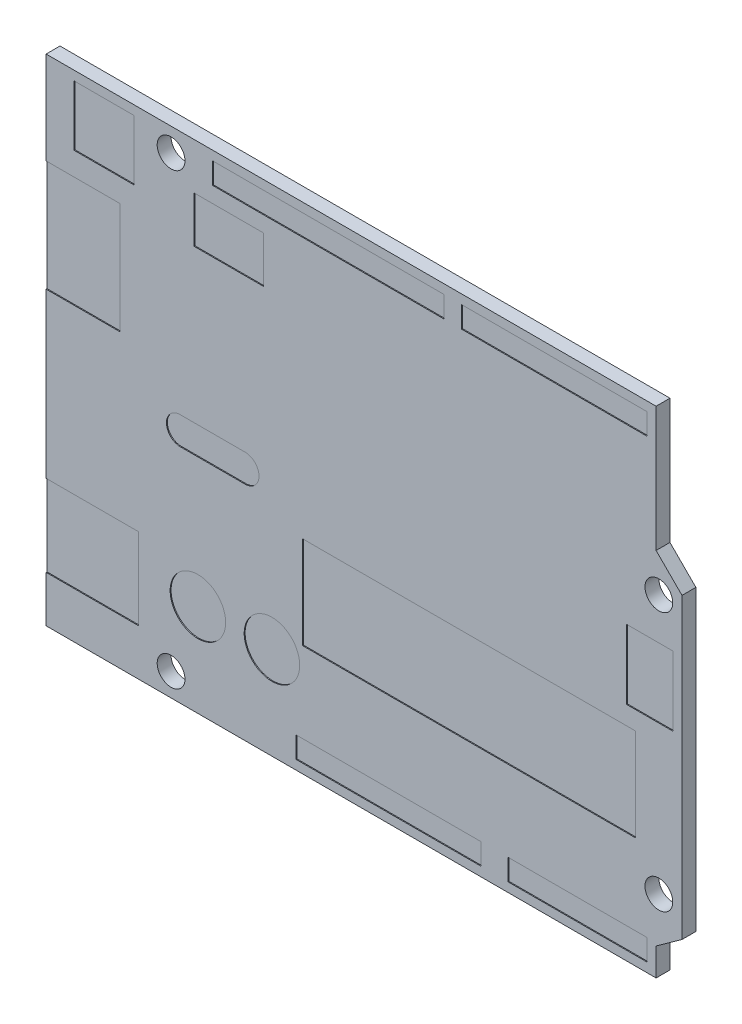
SolidWorks part; units mm, degrees
ref_plane "Plan de face" through (0, 0, 0) normal (0, 0, 1) x (1, 0, 0)
ref_plane "Plan de dessus" through (0, 0, 0) normal (0, 1, 0) x (1, 0, 0)
ref_plane "Plan de droite" through (0, 0, 0) normal (1, 0, 0) x (0, 0, -1)
sketch "Esquisse1" plane through (0, 0, 0) normal (0, 0, 1) x (1, 0, 0)
  line L0 (35.75, 10.45) -> (35.75, -21.75)
  line L1 (-32.95, -26.75) -> (32.95, -26.75)
  line L2 (-32.95, -26.75) -> (-32.95, 26.75)
  line L3 (-32.95, 26.75) -> (32.95, 26.75)
  line L4 (32.95, -26.75) -> (32.95, -23.75)
  line L5 (-32.95, -26.75) -> (32.95, 26.75) construction
  line L6 (-32.95, 26.75) -> (32.95, -26.75) construction
  line L7 (35.75, -21.75) -> (32.95, -23.75)
  line L8 (35.75, 10.45) -> (32.95, 13.25)
  line L9 (32.95, 13.25) -> (32.95, 26.75)
  line L10 (34.75, 8.9034) -> (34.75, -16.2642) construction
  line L11 (33.25, 9.25) -> (33.25, -18.75) construction
  line L12 (0, 0) -> (-23.2773, 0) construction
  circle A0 centre (33.25, 9.25) radius 1.5
  circle A1 centre (33.25, -18.75) radius 1.5
  circle A2 centre (-19.45, 24.25) radius 1.5
  circle A3 centre (-19.45, -24.25) radius 1.5
  point P0 (0, 0)
  dimension "D9" = 3
  dimension "D11" = 8
  dimension "D1" = 65.9
  dimension "D2" = 53.5
  dimension "D3" = 2.8
  dimension "D4" = 32.2
  dimension "D5" = 5
  dimension "D6" = 3
  dimension "D7" = 13.5
  dimension "D8" = 1
  dimension "D10" = 28
  dimension "D12" = 2.5
  dimension "D13" = 13.5
extrude "Boss.-Extru.1" add sketch "Esquisse1" along normal blind 1.5
sketch "Esquisse2" plane through (0, 0, 1.5) normal (0, 0, 1) x (1, 0, 0)
  line L0 (32.95, 26.75) -> (-32.95, 26.75) construction
  line L1 (-29.95, 25.75) -> (-23.45, 25.75)
  line L2 (-29.95, 25.75) -> (-29.95, 19.25)
  line L3 (-29.95, 19.25) -> (-23.45, 19.25)
  line L4 (-23.45, 25.75) -> (-23.45, 19.25)
  line L5 (-29.95, 25.75) -> (-23.45, 19.25) construction
  line L6 (-29.95, 19.25) -> (-23.45, 25.75) construction
  line L7 (-32.95, 26.75) -> (-32.95, -26.75) construction
  line L8 (-18.45, -1.25) -> (-11.45, -1.25) construction
  line L9 (-18.45, 0.25) -> (-11.45, 0.25)
  line L10 (-18.45, -2.75) -> (-11.45, -2.75)
  line L11 (-32.95, -26.75) -> (32.95, -26.75) construction
  line L12 (35.75, -21.75) -> (35.75, 10.45) construction
  line L13 (-5.25, -4.75) -> (30.75, -4.75)
  line L14 (-5.25, -4.75) -> (-5.25, -14.75)
  line L15 (-5.25, -14.75) -> (30.75, -14.75)
  line L16 (30.75, -4.75) -> (30.75, -14.75)
  line L17 (-5.25, -4.75) -> (30.75, -14.75) construction
  line L18 (-5.25, -14.75) -> (30.75, -4.75) construction
  line L19 (32.95, -26.75) -> (32.95, -23.75) construction
  line L20 (29.75, 4.75) -> (34.75, 4.75)
  line L21 (29.75, 4.75) -> (29.75, -2.75)
  line L22 (29.75, -2.75) -> (34.75, -2.75)
  line L23 (34.75, 4.75) -> (34.75, -2.75)
  line L24 (29.75, 4.75) -> (34.75, -2.75) construction
  line L25 (29.75, -2.75) -> (34.75, 4.75) construction
  line L26 (-5.95, -23.45) -> (14.05, -23.45)
  line L27 (-5.95, -23.45) -> (-5.95, -25.75)
  line L28 (-5.95, -25.75) -> (14.05, -25.75)
  line L29 (14.05, -23.45) -> (14.05, -25.75)
  line L30 (-5.95, -23.45) -> (14.05, -25.75) construction
  line L31 (-5.95, -25.75) -> (14.05, -23.45) construction
  line L32 (16.95, -23.45) -> (31.95, -23.45)
  line L33 (16.95, -23.45) -> (16.95, -25.75)
  line L34 (16.95, -25.75) -> (31.95, -25.75)
  line L35 (31.95, -23.45) -> (31.95, -25.75)
  line L36 (16.95, -23.45) -> (31.95, -25.75) construction
  line L37 (16.95, -25.75) -> (31.95, -23.45) construction
  line L38 (-33.7473, -12.95) -> (-22.95, -12.95)
  line L39 (-33.7473, -12.95) -> (-33.7473, -21.75)
  line L40 (-33.7473, -21.75) -> (-22.95, -21.75)
  line L41 (-22.95, -12.95) -> (-22.95, -21.75)
  line L42 (-33.7473, -12.95) -> (-22.95, -21.75) construction
  line L43 (-33.7473, -21.75) -> (-22.95, -12.95) construction
  line L44 (-36.8663, 16.75) -> (-24.95, 16.75)
  line L45 (-36.8663, 16.75) -> (-36.8663, 4.75)
  line L46 (-36.8663, 4.75) -> (-24.95, 4.75)
  line L47 (-24.95, 16.75) -> (-24.95, 4.75)
  line L48 (-36.8663, 16.75) -> (-24.95, 4.75) construction
  line L49 (-36.8663, 4.75) -> (-24.95, 16.75) construction
  line L50 (-14.95, 25.75) -> (10.05, 25.75)
  line L51 (-14.95, 25.75) -> (-14.95, 23.45)
  line L52 (-14.95, 23.45) -> (10.05, 23.45)
  line L53 (10.05, 25.75) -> (10.05, 23.45)
  line L54 (-14.95, 25.75) -> (10.05, 23.45) construction
  line L55 (-14.95, 23.45) -> (10.05, 25.75) construction
  line L56 (11.95, 25.75) -> (31.95, 25.75)
  line L57 (11.95, 25.75) -> (11.95, 23.45)
  line L58 (11.95, 23.45) -> (31.95, 23.45)
  line L59 (31.95, 25.75) -> (31.95, 23.45)
  line L60 (11.95, 25.75) -> (31.95, 23.45) construction
  line L61 (11.95, 23.45) -> (31.95, 25.75) construction
  line L63 (32.95, 13.25) -> (32.95, 26.75) construction
  line L65 (-16.95, 21.75) -> (-9.45, 21.75)
  line L66 (-16.95, 21.75) -> (-16.95, 16.75)
  line L67 (-16.95, 16.75) -> (-9.45, 16.75)
  line L68 (-9.45, 21.75) -> (-9.45, 16.75)
  line L69 (-16.95, 21.75) -> (-9.45, 16.75) construction
  line L70 (-16.95, 16.75) -> (-9.45, 21.75) construction
  arc A0 (-18.45, 0.25) -> (-18.45, -2.75) centre (-18.45, -1.25) ccw
  arc A1 (-11.45, -2.75) -> (-11.45, 0.25) centre (-11.45, -1.25) ccw
  circle A2 centre (-16.55, -16.75) radius 3
  circle A3 centre (-8.55, -16.75) radius 3
  point P0 (-26.7, 22.5)
  point P10 (-14.95, -1.25)
  point P16 (-19.95, -1.25)
  point P17 (-9.95, -1.25)
  point P24 (12.75, -9.75)
  point P32 (32.25, 1)
  point P36 (4.05, -24.6)
  point P41 (24.45, -24.6)
  point P46 (-28.3486, -17.35)
  point P51 (-30.9081, 10.75)
  point P56 (-2.45, 24.6)
  point P68 (32.95, -25.25)
  point P84 (-13.2, 19.25)
  dimension "D33" = 6
  dimension "D34" = 6
  dimension "D1" = 6.5
  dimension "D2" = 6.5
  dimension "D3" = 1
  dimension "D4" = 3
  dimension "D5" = 10
  dimension "D6" = 3
  dimension "D7" = 24
  dimension "D8" = 13
  dimension "D9" = 36
  dimension "D10" = 10
  dimension "D11" = 5
  dimension "D12" = 12
  dimension "D13" = 1
  dimension "D14" = 1
  dimension "D15" = 2.3
  dimension "D16" = 15
  dimension "D17" = 1
  dimension "D18" = 2.3
  dimension "D19" = 20
  dimension "D20" = 27
  dimension "D21" = 5
  dimension "D22" = 7.5
  dimension "D23" = 1
  dimension "D24" = 19
  dimension "D25" = 25
  dimension "D26" = 1
  dimension "D27" = 2.3
  dimension "D28" = 18
  dimension "D29" = 2.3
  dimension "D30" = 1
  dimension "D31" = 20
  dimension "D32" = 1
  dimension "D35" = 10
  dimension "D36" = 16.4
  dimension "D37" = 8
  dimension "D38" = 8.8
  dimension "D39" = 10
  dimension "D40" = 12
  dimension "D41" = 10
  dimension "D42" = 8
  dimension "D43" = 7.5
  dimension "D44" = 5
  dimension "D45" = 16
  dimension "D46" = 5
  dimension "D47" = 5
extrude "Enlèv. mat.-Extru.1" cut sketch "Esquisse2" against normal blind 0.1
